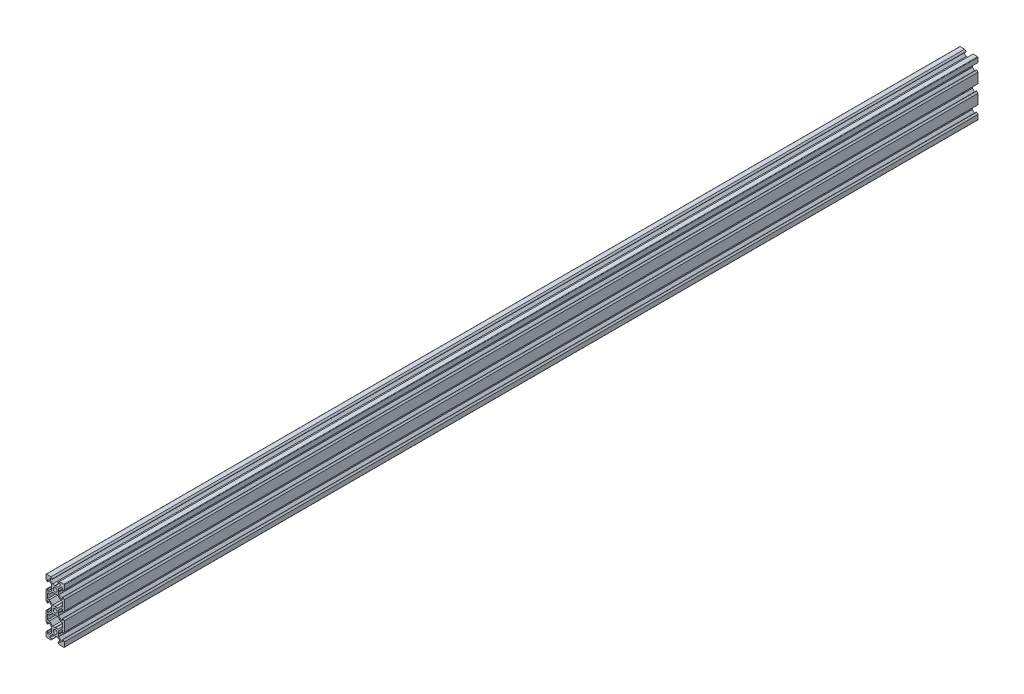
SolidWorks part; units mm, degrees
material "6063-T5"
ref_plane "Front Plane" through (0, 0, 0) normal (0, 0, 1) x (1, 0, 0)
ref_plane "Top Plane" through (0, 0, 0) normal (0, 1, 0) x (1, 0, 0)
ref_plane "Right Plane" through (0, 0, 0) normal (1, 0, 0) x (0, 0, -1)
sketch "Sketch2" plane through (0, 0, 0) normal (0, 0, 1) x (1, 0, 0)
  line L0 (-9.5, 10) -> (-4.58, 10)
  line L1 (-10, 10) -> (10, 10) construction
  line L2 (-10, 10) -> (-10, -10) construction
  line L3 (-10, -10) -> (10, -10) construction
  line L4 (10, 10) -> (10, -10) construction
  line L5 (-10, 10) -> (10, -10) construction
  line L6 (-10, -10) -> (10, 10) construction
  line L7 (-2.84, 3.9) -> (-0.21, 3.9)
  line L8 (-3.9, 2.84) -> (-3.9, 0.21)
  line L11 (-3.9, 3.9) -> (3.9, -3.9) construction
  line L12 (-3.9, -3.9) -> (3.9, 3.9) construction
  line L15 (-3.13, 8.2) -> (-5.5, 8.2)
  line L16 (-5.5, 8.2) -> (-5.5, 6.56)
  line L17 (0, 10) -> (0, -10) construction
  line L18 (-10, 0) -> (10, 0) construction
  line L20 (-10, 9.5) -> (-10, 4.58)
  line L21 (-10, 4.58) -> (-8.55, 3.13)
  line L22 (-8.55, 3.13) -> (-8.2, 3.13)
  line L27 (6.56, 5.5) -> (3.9, 2.84)
  line L30 (4.58, 10) -> (3.13, 8.55)
  line L35 (10, 4.58) -> (8.55, 3.13)
  line L36 (10, 9.5) -> (10, 4.58)
  line L37 (8.55, 3.13) -> (8.2, 3.13)
  line L40 (8.2, -5.5) -> (6.56, -5.5)
  line L41 (8.2, -3.13) -> (8.2, -5.5)
  line L42 (10, -4.58) -> (8.55, -3.13)
  line L43 (8.55, -3.13) -> (8.2, -3.13)
  line L44 (10, -10) -> (10, -4.58)
  line L57 (-8.2, -5.5) -> (-6.56, -5.5)
  line L58 (-8.2, -3.13) -> (-8.2, -5.5)
  line L59 (-10, -4.58) -> (-8.55, -3.13)
  line L60 (-10, -10) -> (-10, -4.58)
  line L61 (-8.55, -3.13) -> (-8.2, -3.13)
  line L62 (-0.21, 3.9) -> (0, 3.69)
  line L63 (0, 3.69) -> (0.21, 3.9)
  line L64 (0.21, 3.9) -> (2.84, 3.9)
  line L65 (3.69, 0) -> (3.9, -0.21)
  line L66 (3.9, 0.21) -> (3.69, 0)
  line L68 (0.21, -3.9) -> (0, -3.69)
  line L71 (3.9, -0.21) -> (3.9, -2.84)
  line L72 (-3.9, -0.21) -> (-3.9, -2.84)
  line L74 (-8.2, -7.3) -> (-8.2, -12.7)
  line L75 (-3.9, -39.79) -> (-3.69, -40)
  line L76 (-3.69, -40) -> (-3.9, -40.21)
  line L77 (-4.58, -10) -> (-3.13, -8.55) [skipped]
  line L78 (-0.21, -36.1) -> (0, -36.31)
  line L79 (-10, -10) -> (-4.58, -10) [skipped]
  line L80 (-2.84, -3.9) -> (-6.24, -7.3)
  line L82 (-8.2, -7.3) -> (-6.24, -7.3)
  line L84 (0, -36.31) -> (0.21, -36.1)
  line L85 (3.9, -39.79) -> (3.69, -40)
  line L86 (3.69, -40) -> (3.9, -40.21)
  line L87 (-0.21, -43.9) -> (0, -43.69)
  line L88 (0, -43.69) -> (0.21, -43.9)
  line L89 (-3.9, -39.79) -> (-3.9, -37.16)
  line L90 (2.84, -3.9) -> (6.24, -7.3)
  line L91 (8.2, -7.3) -> (8.2, -10)
  line L92 (6.24, -7.3) -> (8.2, -7.3)
  line L94 (-2.84, -16.1) -> (-0.21, -16.1)
  line L95 (-3.9, -17.16) -> (-3.9, -19.79)
  line L96 (-2.84, -23.9) -> (-0.21, -23.9)
  line L97 (3.9, -17.16) -> (3.9, -19.79)
  line L98 (2.84, -16.1) -> (6.24, -12.7)
  line L99 (-2.84, -16.1) -> (-6.24, -12.7)
  line L100 (0.21, -36.1) -> (2.84, -36.1)
  line L101 (8.2, -10) -> (8.2, -12.7)
  line L102 (6.24, -12.7) -> (8.2, -12.7)
  line L103 (-10, -10) -> (-10, -15.42)
  line L104 (-10, -15.42) -> (-8.55, -16.87)
  line L105 (-8.55, -16.87) -> (-8.2, -16.87)
  line L106 (-8.2, -16.87) -> (-8.2, -14.5)
  line L107 (-8.2, -14.5) -> (-6.56, -14.5)
  line L108 (-6.56, -14.5) -> (-3.9, -17.16)
  line L109 (-8.2, -12.7) -> (-6.24, -12.7)
  line L110 (6.56, -14.5) -> (3.9, -17.16)
  line L111 (4.58, -50) -> (3.13, -48.55)
  line L113 (-10, -30) -> (-10, -50) construction
  line L114 (-10, -50) -> (10, -50) construction
  line L115 (10, -30) -> (10, -50) construction
  line L116 (8.2, -14.5) -> (6.56, -14.5)
  line L117 (8.2, -16.87) -> (8.2, -14.5)
  line L118 (10, -15.42) -> (8.55, -16.87)
  line L119 (10, -10) -> (10, -15.42)
  line L120 (8.55, -16.87) -> (8.2, -16.87)
  line L121 (6.56, -25.5) -> (3.9, -22.84)
  line L122 (8.2, -25.5) -> (6.56, -25.5)
  line L123 (8.2, -23.13) -> (8.2, -25.5)
  line L124 (10, -24.58) -> (8.55, -23.13)
  line L125 (8.55, -23.13) -> (8.2, -23.13)
  line L126 (10, -30) -> (10, -24.58)
  line L127 (-6.56, -25.5) -> (-3.9, -22.84)
  line L128 (-8.2, -25.5) -> (-6.56, -25.5)
  line L129 (-8.2, -23.13) -> (-8.2, -25.5)
  line L130 (-10, -24.58) -> (-8.55, -23.13)
  line L131 (-10, -30) -> (-10, -24.58)
  line L132 (-8.55, -23.13) -> (-8.2, -23.13)
  line L133 (-0.21, -16.1) -> (0, -16.31)
  line L134 (0, -16.31) -> (0.21, -16.1)
  line L135 (0.21, -16.1) -> (2.84, -16.1)
  line L136 (3.69, -20) -> (3.9, -20.21)
  line L137 (3.9, -19.79) -> (3.69, -20)
  line L138 (0, -23.69) -> (-0.21, -23.9)
  line L139 (0.21, -23.9) -> (0, -23.69)
  line L140 (-3.69, -20) -> (-3.9, -19.79)
  line L141 (-3.9, -20.21) -> (-3.69, -20)
  line L142 (3.9, -20.21) -> (3.9, -22.84)
  line L143 (-3.9, -20.21) -> (-3.9, -22.84)
  line L144 (0.21, -23.9) -> (2.84, -23.9)
  line L145 (-2.84, -23.9) -> (-6.24, -27.3)
  line L146 (-8.2, -27.3) -> (-8.2, -32.7)
  line L147 (-8.2, -27.3) -> (-6.24, -27.3)
  line L148 (2.84, -23.9) -> (6.24, -27.3)
  line L149 (8.2, -27.3) -> (8.2, -30)
  line L150 (6.24, -27.3) -> (8.2, -27.3)
  line L151 (-10, -10) -> (10, -10) construction
  line L152 (-10, -10) -> (-10, -30) construction
  line L153 (-10, -30) -> (10, -30) construction
  line L154 (10, -10) -> (10, -30) construction
  line L155 (-10, -10) -> (10, -30) construction
  line L156 (-10, -30) -> (10, -10) construction
  line L157 (-3.9, -16.1) -> (3.9, -23.9) construction
  line L158 (-3.9, -23.9) -> (3.9, -16.1) construction
  line L159 (0, -10) -> (0, -30) construction
  line L160 (-10, -20) -> (10, -20) construction
  line L161 (3.9, -39.79) -> (3.9, -37.16)
  line L162 (0.21, -43.9) -> (2.84, -43.9)
  line L163 (-2.84, -3.9) -> (-0.21, -3.9)
  line L164 (3.9, 2.84) -> (3.9, 0.21)
  line L165 (-4.58, 10) -> (-3.13, 8.55)
  line L166 (-3.13, 8.55) -> (-3.13, 8.2)
  line L169 (-5.5, 6.56) -> (-2.84, 3.9)
  line L173 (-8.2, 3.13) -> (-8.2, 5.5)
  line L174 (-8.2, 5.5) -> (-6.56, 5.5)
  line L175 (-6.56, 5.5) -> (-3.9, 2.84)
  line L176 (5.5, 6.56) -> (2.84, 3.9)
  line L178 (5.5, 8.2) -> (5.5, 6.56)
  line L179 (3.13, 8.2) -> (5.5, 8.2)
  line L181 (3.13, 8.55) -> (3.13, 8.2)
  line L182 (8.2, 5.5) -> (6.56, 5.5)
  line L183 (8.2, 3.13) -> (8.2, 5.5)
  line L187 (6.56, -5.5) -> (3.9, -2.84)
  line L193 (-6.56, -5.5) -> (-3.9, -2.84)
  line L204 (0, -3.69) -> (-0.21, -3.9)
  line L206 (-3.69, 0) -> (-3.9, 0.21)
  line L207 (-3.9, -0.21) -> (-3.69, 0)
  line L210 (0.21, -3.9) -> (2.84, -3.9)
  line L213 (-10, 10) -> (-10, -10) construction
  line L214 (10, 10) -> (10, -10) construction
  line L215 (-10, 10) -> (10, -10) construction
  line L216 (-10, -10) -> (10, 10) construction
  line L217 (-3.9, 3.9) -> (3.9, -3.9) construction
  line L218 (-3.9, -3.9) -> (3.9, 3.9) construction
  line L219 (0, 10) -> (0, -10) construction
  line L220 (-10, 0) -> (10, 0) construction
  line L222 (9.5, 10) -> (4.58, 10)
  line L227 (3.13, -48.55) -> (3.13, -48.2)
  line L228 (3.13, -48.2) -> (5.5, -48.2)
  line L229 (5.5, -48.2) -> (5.5, -46.56)
  line L230 (-10, -50) -> (10, -30) construction
  line L231 (-10, -30) -> (10, -50) construction
  line L232 (0, -30) -> (0, -50) construction
  line L233 (-10, -40) -> (10, -40) construction
  line L234 (5.5, -46.56) -> (2.84, -43.9)
  line L235 (-2.84, -43.9) -> (-0.21, -43.9)
  line L236 (-3.9, -42.84) -> (-3.9, -40.21)
  line L237 (-2.84, -36.1) -> (-0.21, -36.1)
  line L238 (3.9, -42.84) -> (3.9, -40.21)
  line L239 (-3.9, -43.9) -> (3.9, -36.1) construction
  line L240 (-3.9, -36.1) -> (3.9, -43.9) construction
  line L241 (4.58, -50) -> (9.5, -50)
  line L242 (6.56, -45.5) -> (3.9, -42.84)
  line L243 (8.2, -45.5) -> (6.56, -45.5)
  line L244 (8.2, -43.13) -> (8.2, -45.5)
  line L245 (8.55, -43.13) -> (8.2, -43.13)
  line L246 (10, -44.58) -> (8.55, -43.13)
  line L247 (10, -44.58) -> (10, -49.5)
  line L248 (-4.58, -50) -> (-3.13, -48.55)
  line L249 (-3.13, -48.55) -> (-3.13, -48.2)
  line L250 (-3.13, -48.2) -> (-5.5, -48.2)
  line L251 (-5.5, -48.2) -> (-5.5, -46.56)
  line L252 (-5.5, -46.56) -> (-2.84, -43.9)
  line L253 (-4.58, -50) -> (-9.5, -50)
  line L254 (-8.55, -43.13) -> (-8.2, -43.13)
  line L255 (-6.56, -45.5) -> (-3.9, -42.84)
  line L256 (-8.2, -45.5) -> (-6.56, -45.5)
  line L257 (-8.2, -43.13) -> (-8.2, -45.5)
  line L258 (-10, -44.58) -> (-10, -49.5)
  line L259 (-10, -44.58) -> (-8.55, -43.13)
  line L260 (-8.2, -32.7) -> (-6.24, -32.7)
  line L261 (-2.84, -36.1) -> (-6.24, -32.7)
  line L262 (2.84, -36.1) -> (6.24, -32.7)
  line L263 (6.24, -32.7) -> (8.2, -32.7)
  line L264 (8.2, -32.7) -> (8.2, -30)
  line L265 (8.55, -36.87) -> (8.2, -36.87)
  line L266 (-8.55, -36.87) -> (-8.2, -36.87)
  line L267 (8.2, -36.87) -> (8.2, -34.5)
  line L268 (-8.2, -36.87) -> (-8.2, -34.5)
  line L269 (-8.2, -34.5) -> (-6.56, -34.5)
  line L270 (8.2, -34.5) -> (6.56, -34.5)
  line L271 (-6.56, -34.5) -> (-3.9, -37.16)
  line L272 (6.56, -34.5) -> (3.9, -37.16)
  line L273 (10, -35.42) -> (8.55, -36.87)
  line L274 (-10, -35.42) -> (-8.55, -36.87)
  line L275 (-10, -30) -> (-10, -35.42)
  line L276 (10, -30) -> (10, -35.42)
  line L307 (10, 10) -> (4.58, 10) [skipped]
  line L308 (-2.84, 3.9) -> (-0.21, 3.9) [skipped]
  line L309 (0.21, 3.9) -> (2.84, 3.9) [skipped]
  line L310 (-3.9, 2.84) -> (-3.9, 0.21) [skipped]
  line L311 (-3.9, -0.21) -> (-3.9, -2.84) [skipped]
  line L312 (3.9, -0.21) -> (3.9, -2.84) [skipped]
  line L313 (10, -4.58) -> (8.55, -3.13) [skipped]
  line L316 (-10, 10) -> (-10, 4.58) [skipped]
  line L317 (-10, -10) -> (-10, -4.58) [skipped]
  line L318 (-10, 4.58) -> (-8.55, 3.13) [skipped]
  line L319 (-8.55, 3.13) -> (-8.2, 3.13) [skipped]
  line L320 (8.55, 3.13) -> (8.2, 3.13) [skipped]
  line L321 (-8.2, -3.13) -> (-8.2, -5.5) [skipped]
  line L323 (2.84, -3.9) -> (6.24, -7.3) [skipped]
  line L324 (6.56, 5.5) -> (3.9, 2.84) [skipped]
  line L325 (-2.84, -3.9) -> (-6.24, -7.3) [skipped]
  line L326 (-10, -4.58) -> (-8.55, -3.13) [skipped]
  line L328 (8.2, -7.3) -> (8.2, -10) [skipped]
  line L329 (8.2, -3.13) -> (8.2, -5.5) [skipped]
  line L331 (10, 4.58) -> (8.55, 3.13) [skipped]
  line L332 (10, 10) -> (10, 4.58) [skipped]
  line L333 (10, -10) -> (10, -4.58) [skipped]
  line L334 (8.2, -5.5) -> (6.56, -5.5) [skipped]
  line L335 (-8.2, -5.5) -> (-6.56, -5.5) [skipped]
  line L336 (8.55, -3.13) -> (8.2, -3.13) [skipped]
  line L337 (-8.55, -3.13) -> (-8.2, -3.13) [skipped]
  line L338 (-0.21, 3.9) -> (0, 3.69) [skipped]
  line L339 (3.69, 0) -> (3.9, -0.21) [skipped]
  line L340 (-3.9, -0.21) -> (-3.69, 0) [skipped]
  line L341 (0, 3.69) -> (0.21, 3.9) [skipped]
  line L342 (3.9, 0.21) -> (3.69, 0) [skipped]
  line L343 (0, -3.69) -> (-0.21, -3.9) [skipped]
  line L344 (0.21, -3.9) -> (0, -3.69) [skipped]
  line L345 (-3.69, 0) -> (-3.9, 0.21) [skipped]
  line L346 (-8.2, -7.3) -> (-6.24, -7.3) [skipped]
  line L347 (6.24, -7.3) -> (8.2, -7.3) [skipped]
  circle A1 centre (0, -20) radius 2.1
  circle A2 centre (0, 0) radius 2.1
  circle A3 centre (0, -40) radius 2.1
  arc A4 (9.5, -50) -> (10, -49.5) centre (9.5, -49.5) ccw
  arc A5 (-9.5, -50) -> (-10, -49.5) centre (-9.5, -49.5) cw
  arc A6 (10, 9.5) -> (9.5, 10) centre (9.5, 9.5) ccw
  arc A7 (-9.5, 10) -> (-10, 9.5) centre (-9.5, 9.5) ccw
  point P0 (0, 0)
  point P6 (0, 0)
  point P19 (0, 0)
  point P22 (0, 0)
  point P67 (0, -20)
  point P73 (0, 0)
  point P86 (0, 0)
  point P111 (0, -20)
  point P124 (0, -20)
  point P127 (0, -20)
  point P171 (0, -20)
  point P184 (0, -20)
  point P185 (0, 0)
  point P190 (0, 0)
  point P203 (0, 0)
  point P206 (0, 0)
  point P242 (0, -40)
  point P250 (0, 0)
  point P263 (0, 0)
  point P289 (-8.2, -30)
  point P365 (-8.2, -30)
  dimension "D8" = 0.5
  dimension "D9" = 4.2
  dimension "D3" = 0.21
  dimension "D4" = 45
  dimension "D5" = 0.21
  dimension "D6" = 0.21
  dimension "D7" = 0.21
  dimension "D13" = 0.21
  dimension "D22" = 3.13
  dimension "D23" = 0.35
  dimension "D24" = 1.64
  dimension "D18" = 2
  dimension "D19" = 2
  dimension "D11" = 4
  dimension "D15" = 4
extrude "Boss-Extrude2" add sketch "Sketch2" against normal blind 1000
sketch "Sketch3" plane through (-3.9, 0, 0) normal (-1, 0, 0) x (0, 0, 1)
  line L1 (0, -20.21) -> (0, -22.84) construction
  line L3 (-18.5755, -4.58) -> (-18.5755, -35.42) construction
  line L4 (-1000, -4.58) -> (0, -4.58) construction
  line L5 (-1000, -35.42) -> (0, -35.42) construction
  line L6 (-500, 31.7332) -> (-500, -102.4908) construction
  line L7 (-1000, 10) -> (0, 10) construction
  circle A0 centre (-10, -20) radius 2.1
  circle A1 centre (-10, -40) radius 2.1
  circle A2 centre (-10, 0) radius 2.1
  circle A3 centre (-990, 0) radius 2.1
  circle A4 centre (-990, -40) radius 2.1
  circle A5 centre (-990, -20) radius 2.1
  point P6 (-18.5755, -20)
  point P19 (-500, 10)
  dimension "D1" = 4.2
  dimension "D2" = 10
  dimension "D3" = 2
  dimension "D4" = 2
extrude "Cut-Extrude1" cut sketch "Sketch3" against normal blind 10
